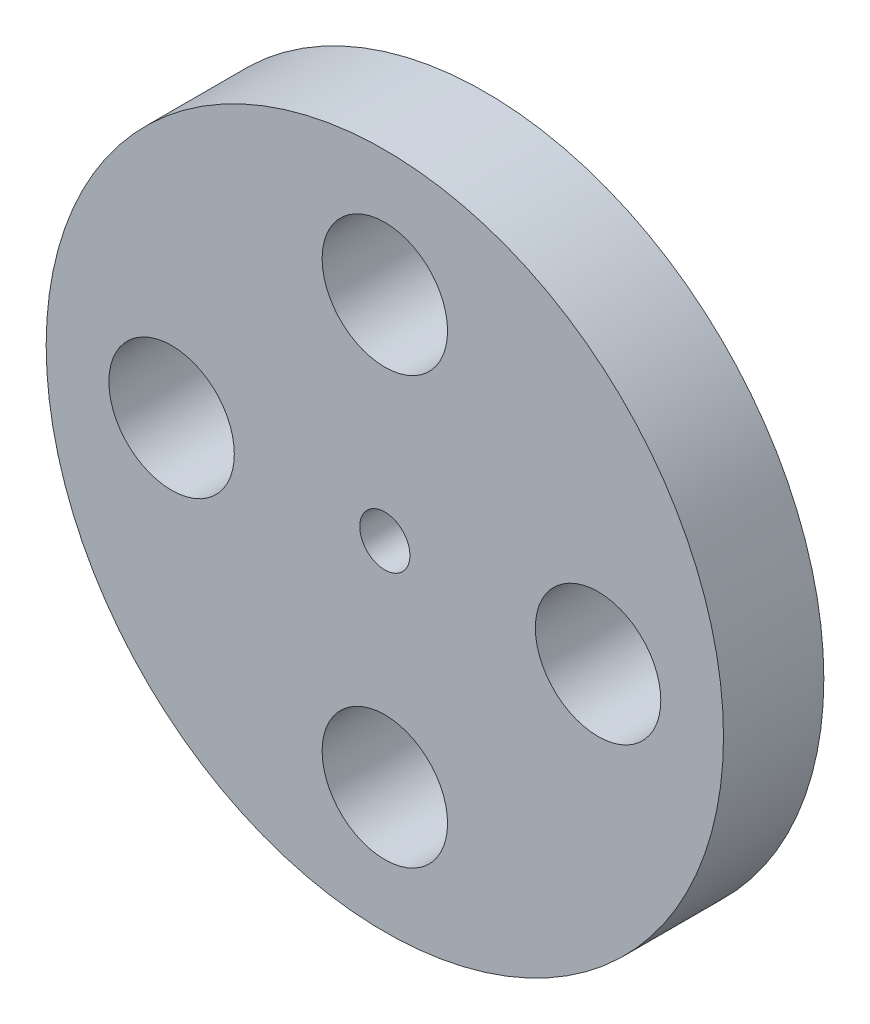
SolidWorks part; units mm, degrees
ref_plane "Front Plane" through (0, 0, 0) normal (0, 0, 1) x (1, 0, 0)
ref_plane "Top Plane" through (0, 0, 0) normal (0, 1, 0) x (1, 0, 0)
ref_plane "Right Plane" through (0, 0, 0) normal (1, 0, 0) x (0, 0, -1)
sketch "Sketch1" plane through (0, 0, 0) normal (0, 0, 1) x (1, 0, 0)
  circle A0 centre (0, 0) radius 13.5
  dimension "D1" = 27
extrude "Boss-Extrude1" add sketch "Sketch1" along normal blind 4
sketch "Sketch2" plane through (0, 0, 4) normal (0, 0, 1) x (1, 0, 0)
  circle A0 centre (0, 0) radius 1
  dimension "D1" = 2
extrude "Cut-Extrude1" cut sketch "Sketch2" against normal up to next
sketch "Sketch3" plane through (0, 0, 0) normal (0, 0, -1) x (-1, 0, 0)
  line L0 (-15.5729, 0) -> (17.5388, 0) construction
  line L1 (0, 14.0719) -> (0, -14.607) construction
  circle A0 centre (0, 8.5) radius 2.5
  dimension "D1" = 5
  dimension "D2" = 8.5
extrude "Cut-Extrude2" cut sketch "Sketch3" against normal up to next
mirror "Mirror1" about plane through (0, 0, 0) normal (0, 1, 0) of "Cut-Extrude2"
sketch "Sketch4" plane through (0, 0, 0) normal (0, 0, -1) x (-1, 0, 0)
  circle A0 centre (8.5, 0) radius 2.5
  dimension "D1" = 5
  dimension "D2" = 8.5
extrude "Cut-Extrude3" cut sketch "Sketch4" against normal up to next
sketch "Sketch5" plane through (0, 0, 0) normal (0, 0, -1) x (-1, 0, 0)
  circle A0 centre (-8.5, 0) radius 2.5
  dimension "D1" = 5
  dimension "D2" = 8.5
extrude "Cut-Extrude4" cut sketch "Sketch5" against normal up to next
